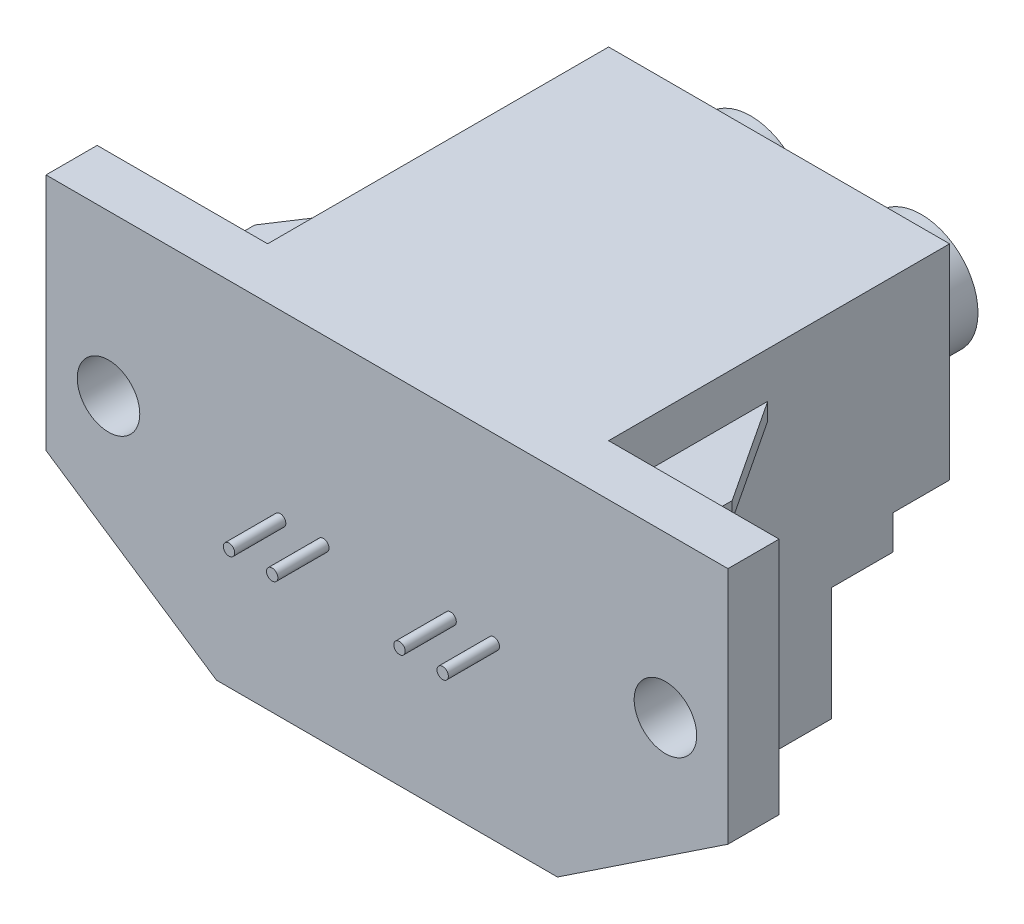
SolidWorks part; units mm, degrees
ref_plane "Спереди" through (0, 0, 0) normal (0, 0, 1) x (1, 0, 0)
ref_plane "Сверху" through (0, 0, 0) normal (0, 1, 0) x (1, 0, 0)
ref_plane "Справа" through (0, 0, 0) normal (1, 0, 0) x (0, 0, -1)
sketch "Эскиз1" plane through (0, 0, 0) normal (0, 0, 1) x (1, 0, 0)
  line L0 (-61.4223, 0) -> (72.2783, 0) construction
  line L1 (0, 51.5662) -> (0, -42.4242) construction
  line L2 (-15, -16.9) -> (-30, -6.9)
  line L3 (-15, -16.9) -> (15, -16.9)
  line L4 (-30, -6.9) -> (-30, 14.1)
  line L5 (-30, 14.1) -> (30, 14.1)
  line L6 (30, -6.9) -> (30, 14.1)
  line L7 (15, -16.9) -> (30, -6.9)
  circle A0 centre (-24.5, 0) radius 2.75
  circle A1 centre (24.5, 0) radius 2.75
  dimension "D6" = 5.5
  dimension "D7" = 49
  dimension "D1" = 31
  dimension "D2" = 60
  dimension "D3" = 14.1
  dimension "D4" = 15
  dimension "D5" = 10
extrude "Вытянуть1" add sketch "Эскиз1" along normal blind 4.5
sketch "Эскиз2" plane through (0, 0, 0) normal (1, 0, 0) x (0, 0, -1)
  line L0 (-4.5, 14.1) -> (0, 14.1) construction
  line L1 (0, -16.9) -> (19.6045, -16.9)
  line L2 (0, -16.9) -> (0, 14.1)
  line L3 (0, 14.1) -> (30, 14.1)
  line L4 (30, -3.9) -> (30, 14.1)
  line L5 (-4.5, -16.9) -> (0, -16.9) construction
  line L8 (19.6045, -16.9) -> (19.6045, -6.9)
  line L9 (19.6045, -6.9) -> (25, -6.9)
  line L10 (25, -6.9) -> (25, -3.9)
  line L11 (25, -3.9) -> (30, -3.9)
  dimension "D1" = 30
  dimension "D2" = 10
  dimension "D3" = 3
  dimension "D4" = 5
extrude "Вытянуть2" add sketch "Эскиз2" along normal blind 15 and the other way blind 15
sketch "Эскиз3" plane through (0, 0, -30) normal (0, 0, -1) x (-1, 0, 0)
  line L0 (0, 19.2629) -> (0, -20.9552) construction
  line L1 (-29.3115, 5.1) -> (29.2263, 5.1) construction
  line L2 (-15, -3.9) -> (15, -3.9) construction
  line L3 (-15, 14.1) -> (15, 14.1) construction
  circle A1 centre (-7.5, 5.1) radius 5
  circle A2 centre (7.5, 5.1) radius 5
  circle A3 centre (-7.5, 5.1) radius 3.5
  circle A5 centre (7.5, 5.1) radius 3.5
  dimension "D1" = 15
  dimension "D2" = 10
extrude "Вытянуть3" add sketch "Эскиз3" along normal blind 5
sketch "Эскиз4" plane through (0, -16.9, 0) normal (0, -1, 0) x (1, 0, 0)
  line L0 (0, 11.2633) -> (0, -37.6461) construction
  line L2 (-31.2713, -7.5523) -> (29.0559, -7.5523) construction
  line L3 (-15, 4.5) -> (15, 4.5) construction
  line L4 (15, -19.6045) -> (-15, -19.6045) construction
  line L11 (2.5, -15.0523) -> (2.5, -0.0523)
  line L12 (12.5, -15.0523) -> (12.5, -0.0523)
  line L13 (12.5, -0.0523) -> (2.5, -0.0523)
  line L14 (12.5, -15.0523) -> (2.5, -15.0523)
  line L15 (-12.5, -15.0523) -> (-12.5, -0.0523)
  line L16 (-2.5, -0.0523) -> (-12.5, -0.0523)
  line L17 (-2.5, -15.0523) -> (-2.5, -0.0523)
  line L18 (-2.5, -15.0523) -> (-12.5, -15.0523)
  dimension "D1" = 10
  dimension "D2" = 15
  dimension "D3" = 2.5
  dimension "D4" = 2.5
extrude "Вырез-Вытянуть1" cut sketch "Эскиз4" against normal blind 5
sketch "Эскиз5" plane through (0, 0, 4.5) normal (0, 0, 1) x (1, 0, 0)
  line L0 (0, 19.3482) -> (0, -23.6819) construction
  line L1 (-39.6217, 0) -> (39.0252, 0) construction
  line L2 (-37.6021, 9.2084) -> (41.0448, 9.2084) construction
  line L3 (-11.6361, 2.9584) -> (10.6352, 2.9584) construction
  line L4 (-15, -16.9) -> (15, -16.9) construction
  circle A4 centre (-9.4, -1.9) radius 0.5
  circle A5 centre (-5.6, -1.9) radius 0.5
  circle A8 centre (5.6, -1.9) radius 0.5
  circle A9 centre (9.4, -1.9) radius 0.5
  dimension "D1" = 15
  dimension "D2" = 15
  dimension "D4" = 3.8
  dimension "D8" = 5.6
  dimension "D9" = 3.8
  dimension "D3" = 15
extrude "Вытянуть4" add sketch "Эскиз5" along normal blind 4.5
sketch "Эскиз6" plane through (0, 0, 0) normal (0, 0, -1) x (-1, 0, 0)
  line L0 (-15, 14.1) -> (-15, -16.9) construction
  line L1 (-21, -8.9) -> (-15, -8.9)
  line L2 (-21, -8.9) -> (-21, -7.4)
  line L3 (-21, -7.4) -> (-15, -7.4)
  line L4 (-15, -8.9) -> (-15, -7.4)
  line L5 (-15, -16.9) -> (15, -16.9) construction
  line L6 (-21, 0.6) -> (15, 0.6) construction
  line L7 (15, 14.1) -> (15, -16.9) construction
  line L8 (0, 18.0386) -> (0, -18.9906) construction
  line L9 (-30, -6.9) -> (-30, 14.1) construction
  line L10 (30, 14.1) -> (30, -6.9) construction
  line L11 (-15, 10.1) -> (-15, 8.6)
  line L12 (-21, 8.6) -> (-15, 8.6)
  line L13 (-21, 10.1) -> (-21, 8.6)
  line L14 (-21, 10.1) -> (-15, 10.1)
  line L15 (21, 10.1) -> (15, 10.1)
  line L16 (21, 10.1) -> (21, 8.6)
  line L17 (21, 8.6) -> (15, 8.6)
  line L18 (15, 10.1) -> (15, 8.6)
  line L19 (15, -8.9) -> (15, -7.4)
  line L20 (21, -7.4) -> (15, -7.4)
  line L21 (21, -8.9) -> (21, -7.4)
  line L22 (21, -8.9) -> (15, -8.9)
  dimension "D1" = 8
  dimension "D2" = 1.5
  dimension "D3" = 6
  dimension "D4" = 8
extrude "Вытянуть5" add sketch "Эскиз6" along normal blind 14
sketch "Эскиз7" plane through (0, -8.9, 0) normal (0, -1, 0) x (1, 0, 0)
  line L0 (15, -14) -> (22.1749, -3.0853)
  line L1 (22.1749, -3.0853) -> (22.1749, -17.2999)
  line L2 (22.1749, -17.2999) -> (15, -14)
  line L3 (0, 8.9261) -> (0, -18.8635) construction
  line L4 (-15, 0) -> (-15, -19.6045) construction
  line L5 (15, 0) -> (15, -19.6045) construction
  line L6 (-22.1749, -17.2999) -> (-15, -14)
  line L7 (-22.1749, -3.0853) -> (-22.1749, -17.2999)
  line L8 (-15, -14) -> (-22.1749, -3.0853)
extrude "Вырез-Вытянуть2" cut sketch "Эскиз7" against normal blind 20
